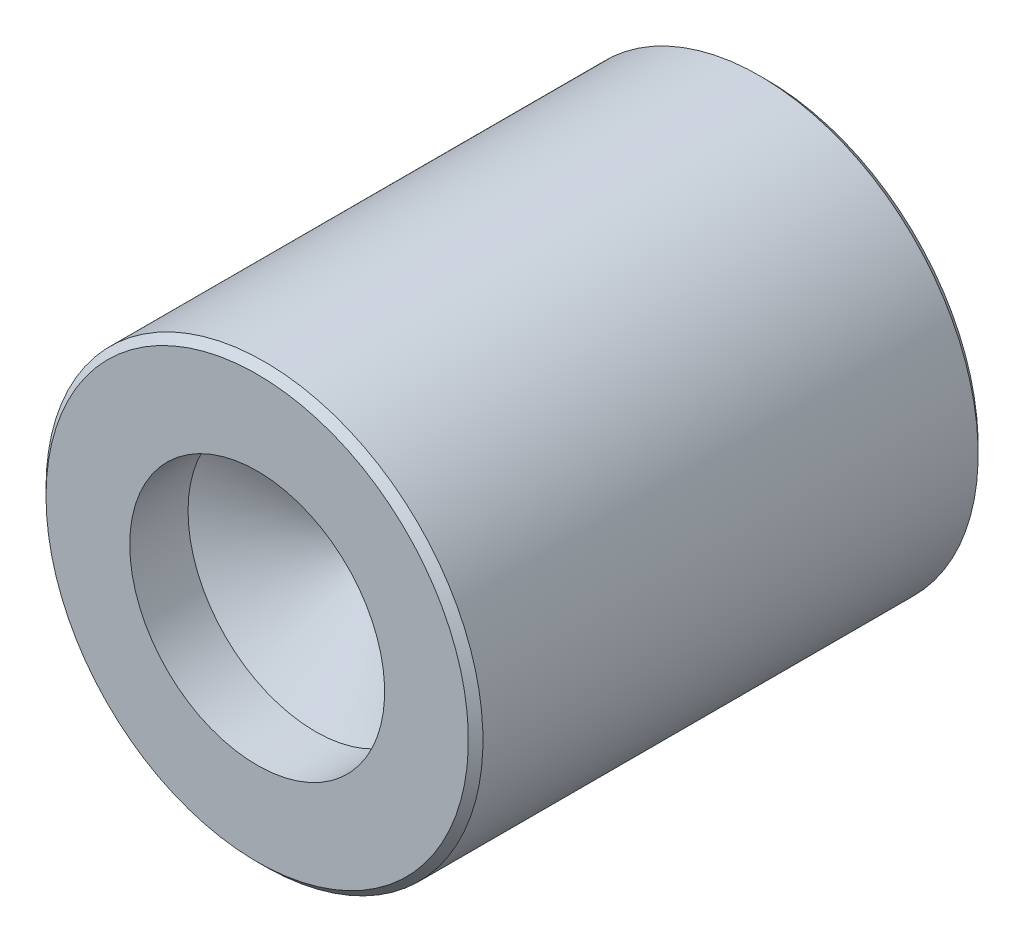
SolidWorks part; units mm, degrees
ref_plane "Plan de face" through (0, 0, 0) normal (0, 0, 1) x (1, 0, 0)
ref_plane "Plan de dessus" through (0, 0, 0) normal (0, 1, 0) x (1, 0, 0)
ref_plane "Plan de droite" through (0, 0, 0) normal (1, 0, 0) x (0, 0, -1)
ref_plane "Plan1" through (0, 0, 0) normal (0, -1, 0) x (1, 0, 0)
sketch "Esquisse1" plane through (0, 0, 0) normal (0, -1, 0) x (1, 0, 0)
  line L0 (17.5, 62) -> (0, 51.4849)
  line L1 (0, 51.4849) -> (0, 0)
  line L2 (0, 0) -> (29, 0)
  line L3 (29, 0) -> (30, 1)
  line L4 (30, 1) -> (30, 69)
  line L5 (30, 69) -> (29, 70)
  line L6 (29, 70) -> (17.5, 70)
  line L7 (17.5, 70) -> (17.5, 62)
  line L8 (0, 70) -> (0, 0) construction
revolve "Révolution1" add sketch "Esquisse1" angle 360 about L8
